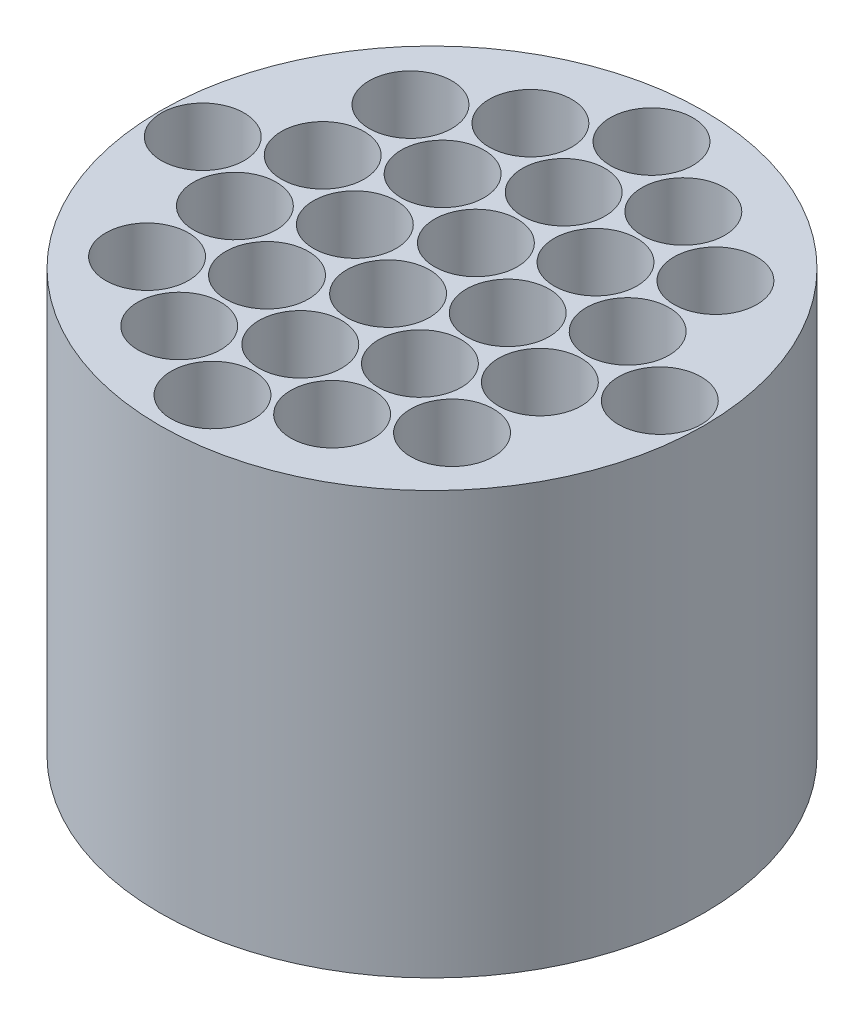
SolidWorks part; units mm, degrees
ref_plane "Front Plane" through (0, 0, 0) normal (0, 0, 1) x (1, 0, 0)
ref_plane "Top Plane" through (0, 0, 0) normal (0, 1, 0) x (1, 0, 0)
ref_plane "Right Plane" through (0, 0, 0) normal (1, 0, 0) x (0, 0, -1)
sketch "Sketch1" plane through (0, 0, 0) normal (0, 1, 0) x (1, 0, 0)
  circle A0 centre (0, 0) radius 16.125
  dimension "D1" = 32.25
extrude "Boss-Extrude1" add sketch "Sketch1" along normal blind 25
sketch "Sketch2" plane through (0, 25, 0) normal (0, 1, 0) x (1, 0, 0)
  line L0 (0, 16.125) -> (0, -16.125) construction
  circle A0 centre (0, -2.6) radius 2.45
  circle A1 centre (0, 2.6) radius 2.45
  circle A2 centre (0, 7.8) radius 2.45
  circle A3 centre (0, 13) radius 2.45
  circle A4 centre (0, 0) radius 16.125 construction
  circle A13 centre (0, -7.8) radius 2.45
  circle A14 centre (0, -13) radius 2.45
  dimension "D1" = 4.9
  dimension "D2" = 5.2
  dimension "D3" = 5.2
  dimension "D4" = 5.2
  dimension "D5" = 5.2
  dimension "D6" = 5.2
extrude "Cut-Extrude1" cut sketch "Sketch2" against normal blind 18.75
sketch "Sketch3" plane through (0, 25, 0) normal (0, 1, 0) x (1, 0, 0)
  line L0 (4.528, 15.4762) -> (4.528, -15.4762) construction
  circle A0 centre (4.528, -0.0432) radius 2.45
  circle A1 centre (4.528, 5.1568) radius 2.45
  circle A2 centre (4.528, -5.2432) radius 2.45
  circle A3 centre (4.528, -10.4432) radius 2.45
  circle A4 centre (4.528, 10.3568) radius 2.45
  circle A5 centre (0, 0) radius 16.125 construction
  circle A6 centre (0, 2.6) radius 2.45 construction
  dimension "D1" = 4.9
  dimension "D2" = 5.2
  dimension "D3" = 5.2
  dimension "D4" = 5.2
  dimension "D5" = 5.2
  dimension "D6" = 5.2
extrude "Cut-Extrude2" cut sketch "Sketch3" against normal blind 18.75
sketch "Sketch4" plane through (0, 25, 0) normal (0, 1, 0) x (1, 0, 0)
  line L0 (9.0314, 13.3585) -> (9.0314, -13.3585) construction
  circle A0 centre (0, 0) radius 16.125 construction
  circle A1 centre (9.0314, 7.7568) radius 2.45
  circle A2 centre (9.0314, 2.5568) radius 2.45
  circle A3 centre (9.0314, -2.6432) radius 2.45
  circle A4 centre (9.0314, -7.8432) radius 2.45
  dimension "D1" = 4.9
  dimension "D2" = 5.2
  dimension "D3" = 5.2
  dimension "D4" = 5.2
  dimension "D5" = 5.2
  dimension "D6" = 5.2
extrude "Cut-Extrude3" cut sketch "Sketch4" against normal blind 18.75
sketch "Sketch5" plane through (0, 25, 0) normal (0, 1, 0) x (1, 0, 0)
  circle A0 centre (13.5347, -0.0432) radius 2.45
  dimension "D1" = 4.9
  dimension "D2" = 5.2
  dimension "D3" = 5.2
extrude "Cut-Extrude5" cut sketch "Sketch5" against normal blind 18.75 contours A0
mirror "Mirror2" about plane through (0, 0, 0) normal (1, 0, 0) of "Cut-Extrude2", "Cut-Extrude3", "Cut-Extrude5"
